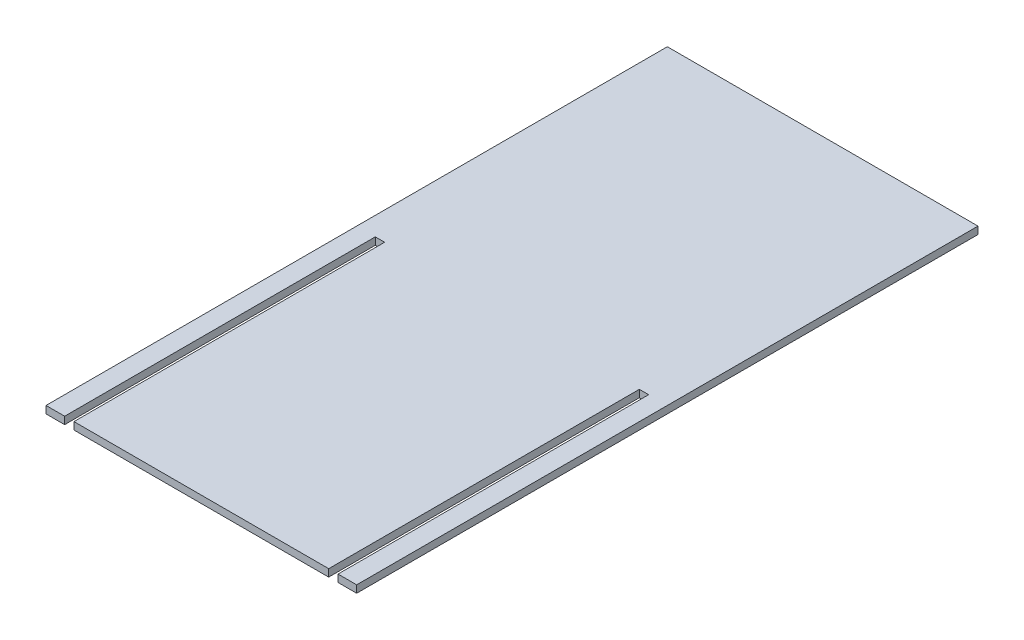
SolidWorks part; units mm, degrees
ref_plane "Front Plane" through (0, 0, 0) normal (0, 0, 1) x (1, 0, 0)
ref_plane "Top Plane" through (0, 0, 0) normal (0, 1, 0) x (1, 0, 0)
ref_plane "Right Plane" through (0, 0, 0) normal (1, 0, 0) x (0, 0, -1)
sketch "Sketch1" plane through (0, 0, 0) normal (0, 1, 0) x (1, 0, 0)
  line L1 (0, 254) -> (127, 254)
  line L2 (0, 254) -> (0, 0)
  line L3 (0, 0) -> (127, 0)
  line L4 (127, 254) -> (127, 0)
  dimension "D1" = 127
  dimension "D2" = 254
extrude "Boss-Extrude1" add sketch "Sketch1" along normal blind 3
sketch "Sketch2" plane through (0, 3, 0) normal (0, 1, 0) x (1, 0, 0)
  line L0 (0, 0) -> (127, 0) construction
  line L1 (7.62, 127) -> (11.43, 127)
  line L2 (7.62, 127) -> (7.62, 0)
  line L3 (7.62, 0) -> (11.43, 0)
  line L4 (11.43, 127) -> (11.43, 0)
  line L5 (0, 254) -> (0, 0) construction
  line L6 (63.5, 254) -> (63.5, 0) construction
  line L7 (127, 254) -> (0, 254) construction
  line L8 (119.38, 0) -> (115.57, 0)
  line L9 (115.57, 127) -> (115.57, 0)
  line L10 (119.38, 127) -> (119.38, 0)
  line L11 (119.38, 127) -> (115.57, 127)
  dimension "D1" = 127
  dimension "D2" = 3.81
  dimension "D3" = 7.62
extrude "Cut-Extrude1" cut sketch "Sketch2" against normal through all
equation "\"Width\" = 5in"
equation "\"Height\" = 10in"
equation "\"D1@Sketch1\"= \"Width\""
equation "\"D2@Sketch1\"= \"Height\""
equation "\"D1@Sketch2\"= \"Height\" / 2"
equation "\"Overhang\" = 0.3in"
equation "\"D2@Sketch2\" = \"Thick\""
equation "\"D3@Sketch2\"= \"Overhang\""
equation "\"Thick\" = 0.15in"
